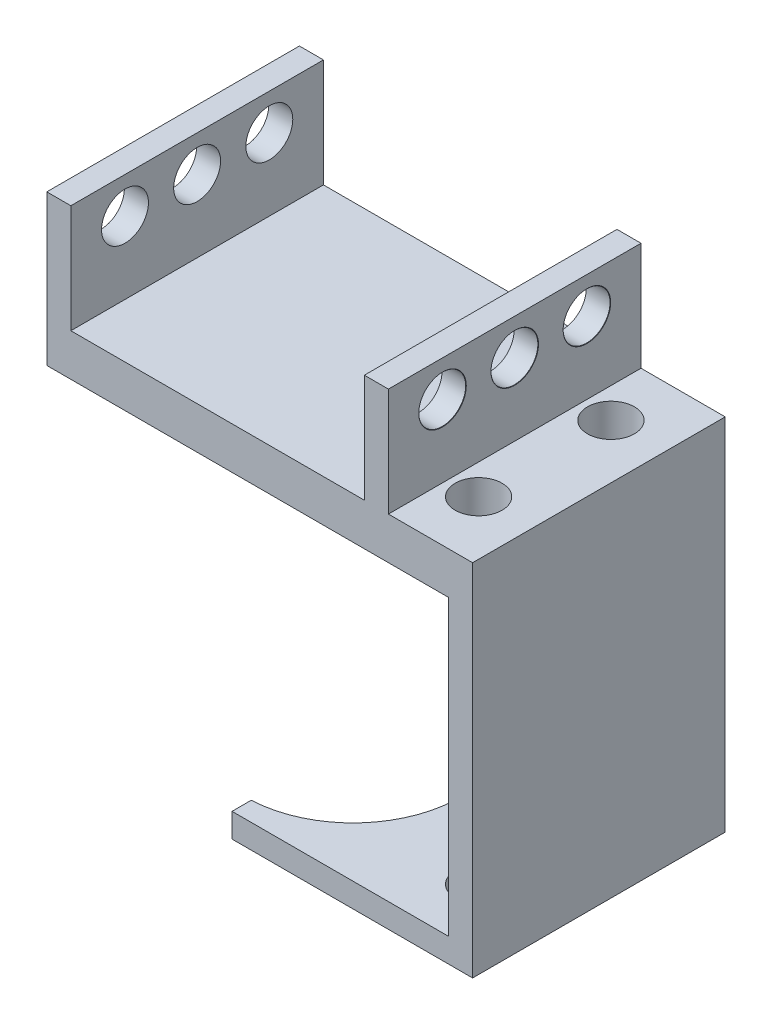
SolidWorks part; units mm, degrees
ref_plane "Front Plane" through (0, 0, 0) normal (0, 0, 1) x (1, 0, 0)
ref_plane "Top Plane" through (0, 0, 0) normal (0, 1, 0) x (1, 0, 0)
ref_plane "Right Plane" through (0, 0, 0) normal (1, 0, 0) x (0, 0, -1)
sketch "Sketch1" plane through (0, 0, 0) normal (0, 0, 1) x (1, 0, 0)
  line L0 (14.421, -30) -> (21.421, -30)
  line L2 (12.421, -21) -> (14.421, -21)
  line L3 (12.421, -21) -> (12.421, -30)
  line L5 (14.421, -21) -> (14.421, -30)
  line L6 (19.421, -33.5) -> (14.421, -33.5)
  line L7 (12.421, -30) -> (-11.979, -30)
  line L12 (-13.979, -33.5) -> (-13.979, -21)
  line L13 (-13.979, -21) -> (-11.979, -21)
  line L14 (-11.979, -30) -> (-11.979, -21)
  line L15 (-11.779, -25.9259) -> (-11.779, -23.0615) construction
  line L16 (14.421, -33.5) -> (-13.979, -33.5)
  line L20 (12.221, -23.0615) -> (12.221, -25.9259) construction
  line L21 (-11.479, -27) -> (-8.779, -27) construction
  line L22 (21.421, -30) -> (21.421, -59.9)
  line L23 (19.421, -57.9) -> (1.421, -57.9)
  line L24 (1.421, -57.9) -> (1.421, -59.9)
  line L25 (1.421, -59.9) -> (21.421, -59.9)
  line L27 (19.421, -33.5) -> (19.421, -57.9)
  line L28 (6.768, -57.5) -> (-21.2839, -57.5) construction
  dimension "D1" = 3.5
  dimension "D2" = 2
  dimension "D3" = 2
  dimension "D4" = 0.2
  dimension "D5" = 9
  dimension "D6" = 0.2
  dimension "D7" = 3
  dimension "D8" = 2
  dimension "D9" = 2
  dimension "D10" = 20
  dimension "D11" = 7
  dimension "D12" = 0.4
extrude "Boss-Extrude1" add sketch "Sketch1" against normal blind 21
hole_wizard "M3.5 Clearance Hole1" positions "Sketch2" profile "Sketch3" hole size "M3.5" standard "ANSI Metric" end condition through all
sketch "Sketch2" plane through (14.421, 0, 0) normal (1, 0, 0) x (0, 0, -1)
  arc A0 (2.5, -24) -> (6.5, -24) centre (4.5, -24) ccw construction
  arc A1 (2.5, -24) -> (6.5, -24) centre (4.5, -24) ccw construction
  arc A2 (8, -24) -> (13, -24) centre (10.5, -24) ccw construction
  arc A3 (8, -24) -> (13, -24) centre (10.5, -24) ccw construction
  arc A4 (8, -24) -> (13, -24) centre (10.5, -24) ccw construction
  arc A5 (8, -24) -> (13, -24) centre (10.5, -24) ccw construction
  arc A6 (14, -24) -> (19, -24) centre (16.5, -24) ccw construction
  arc A7 (14, -24) -> (19, -24) centre (16.5, -24) ccw construction
  point P0 (4.5, -24)
  point P2 (10.5, -24)
  point P4 (16.5, -24)
sketch "Sketch3" plane through (14.421, -24, -4.5) normal (0, 1, 0) x (0, 0, -1)
  line L0 (0, 0) -> (0, 28.4)
  line L1 (0, 28.4) -> (1.95, 28.4)
  line L2 (1.95, 28.4) -> (1.95, 0.025)
  line L3 (1.95, 0.025) -> (1.975, 0)
  line L5 (1.975, 0) -> (0, 0)
  line L6 (-1.95, 0.025) -> (-1.975, 0) construction
  line L11 (0, -6.35) -> (0, 107.95) construction
  dimension "Thru Hole Dia." = 3.9
  dimension "Thru Hole Depth" = 28.4
  dimension "Near C'Sink Dia." = 3.95
  dimension "Near C'Sink Angle" = 90
sketch "Sketch4" plane through (0, -33.5, 0) normal (0, -1, 0) x (1, 0, 0)
  line L14 (14.421, -21) -> (14.421, 0) construction
  circle A7 centre (1.421, -10.5) radius 9
  circle A8 centre (1.421, -10.5) radius 6 construction
  circle A9 centre (1.421, -4.5) radius 2
  circle A10 centre (1.421, -16.5) radius 2
  circle A11 centre (-4.579, -10.5) radius 2
  circle A12 centre (7.421, -10.5) radius 2
  point P6 (2.3007, -10.5)
  point P7 (0.4925, -10.5)
  dimension "D5" = 18
  dimension "D6" = 12
  dimension "D7" = 4
  dimension "D8" = 4
  dimension "D9" = 4
  dimension "D10" = 4
  dimension "D2" = 13
extrude "Cut-Extrude1" cut sketch "Sketch4" against normal blind 3
sketch "Sketch5" plane through (0, -59.9, 0) normal (0, -1, 0) x (1, 0, 0)
  circle A1 centre (0.9948, -10.4848) radius 8.9 construction
  circle A3 centre (0.9948, -10.4848) radius 8.9
extrude "Cut-Extrude2" cut sketch "Sketch5" against normal blind 3
hole_wizard "M3.5 Clearance Hole2" positions "Sketch6" profile "Sketch7" hole size "M3.5" standard "ANSI Metric" end condition through all
sketch "Sketch6" plane through (0, -59.9, 0) normal (0, -1, 0) x (-1, 0, 0)
  line L0 (-21.421, 21) -> (-21.421, 0) construction
  line L1 (-1.421, 21) -> (-21.421, 21) construction
  line L2 (-1.421, 0) -> (-21.421, 0) construction
  point P0 (-16.921, 16)
  point P2 (-16.921, 5)
  point P5 (0, 0)
  point P6 (-18.0461, 15.6858)
  point P7 (-17.546, 15.7293)
  point P8 (-16.9669, 15.7311)
  dimension "D1" = 4.5
  dimension "D2" = 5
  dimension "D3" = 5
sketch "Sketch7" plane through (16.921, -59.9, -16) normal (1, 0, 0) x (0, 0, -1)
  line L0 (0, 0) -> (0, 38.9)
  line L1 (0, 38.9) -> (1.95, 38.9)
  line L2 (1.95, 38.9) -> (1.95, 0.025)
  line L3 (1.95, 0.025) -> (1.975, 0)
  line L5 (1.975, 0) -> (0, 0)
  line L6 (-1.95, 0.025) -> (-1.975, 0) construction
  line L11 (0, -6.35) -> (0, 107.95) construction
  dimension "Thru Hole Dia." = 3.9
  dimension "Thru Hole Depth" = 38.9
  dimension "Near C'Sink Dia." = 3.95
  dimension "Near C'Sink Angle" = 90
